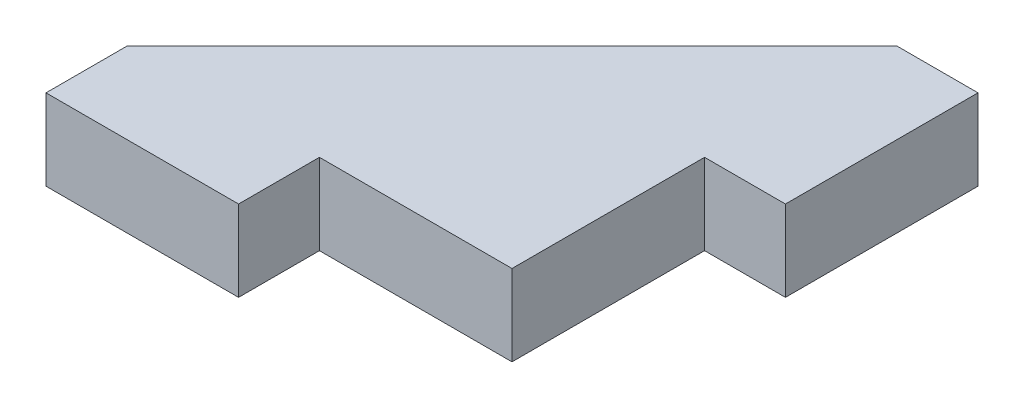
SolidWorks part; units mm, degrees
ref_plane "Front Plane" through (0, 0, 0) normal (0, 0, 1) x (1, 0, 0)
ref_plane "Top Plane" through (0, 0, 0) normal (0, 1, 0) x (1, 0, 0)
ref_plane "Right Plane" through (0, 0, 0) normal (1, 0, 0) x (0, 0, -1)
sketch "Sketch1" plane through (0, 0, 0) normal (0, 1, 0) x (1, 0, 0)
  line L0 (-21.062, -13.6221) -> (4.338, 11.7779)
  line L2 (4.338, 11.7779) -> (9.672, 11.7779)
  line L3 (-21.062, -13.6221) -> (4.338, -13.6221)
  line L4 (4.338, 11.7779) -> (4.338, -13.6221)
  line L5 (4.338, 11.7779) -> (4.338, -0.9221)
  line L6 (4.338, -0.9221) -> (9.672, -0.9221)
  line L7 (9.672, 11.7779) -> (9.672, -0.9221)
  line L8 (-21.062, -13.6221) -> (-8.362, -13.6221)
  line L9 (-21.062, -13.6221) -> (-21.062, -18.9561)
  line L10 (-21.062, -18.9561) -> (-8.362, -18.9561)
  line L11 (-8.362, -13.6221) -> (-8.362, -18.9561)
  dimension "D2" = 25.4
  dimension "D1" = 12.7
  dimension "D3" = 12.7
  dimension "D4" = 5.334
  dimension "D5" = 5.334
extrude "Boss-Extrude1" add sketch "Sketch1" along normal blind 5.334 contours L11 L3 L9 L10 | L4 L0 L3 | L7 L2 L4 L6
equation "\"MDF\"= .21in"
equation "\"Foamcore\"= .13in"
equation "\"Gmaterial\"= \"MDF\""
equation "\"D4@Sketch1\"=\"MDF\""
equation "\"D5@Sketch1\"=\"MDF\""
equation "\"D1@Boss-Extrude1\"=\"MDF\""
